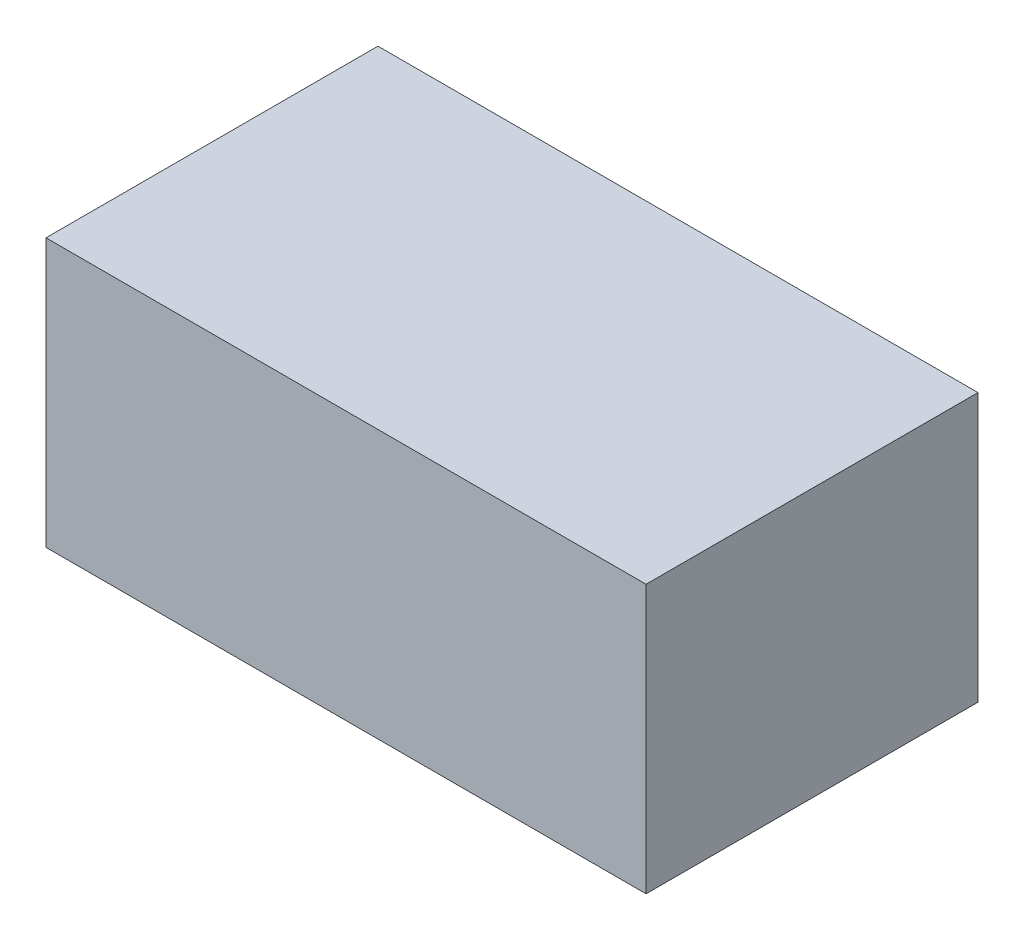
SolidWorks part; units mm, degrees
ref_plane "Front Plane" through (0, 0, 0) normal (0, 0, 1) x (1, 0, 0)
ref_plane "Top Plane" through (0, 0, 0) normal (0, 1, 0) x (1, 0, 0)
ref_plane "Right Plane" through (0, 0, 0) normal (1, 0, 0) x (0, 0, -1)
sketch "Sketch1" plane through (0, 0, 0) normal (0, 1, 0) x (1, 0, 0)
  line L1 (-23.5, 13) -> (23.5, 13)
  line L2 (-23.5, 13) -> (-23.5, -13)
  line L3 (-23.5, -13) -> (23.5, -13)
  line L4 (23.5, 13) -> (23.5, -13)
  line L5 (-23.5, 13) -> (23.5, -13) construction
  line L6 (-23.5, -13) -> (23.5, 13) construction
  point P4 (0, 0)
  point P5 (0, 0)
  dimension "D1" = 47
  dimension "D2" = 26
extrude "Boss-Extrude1" add sketch "Sketch1" along normal blind 21 contours L3 L4 L1 L2
